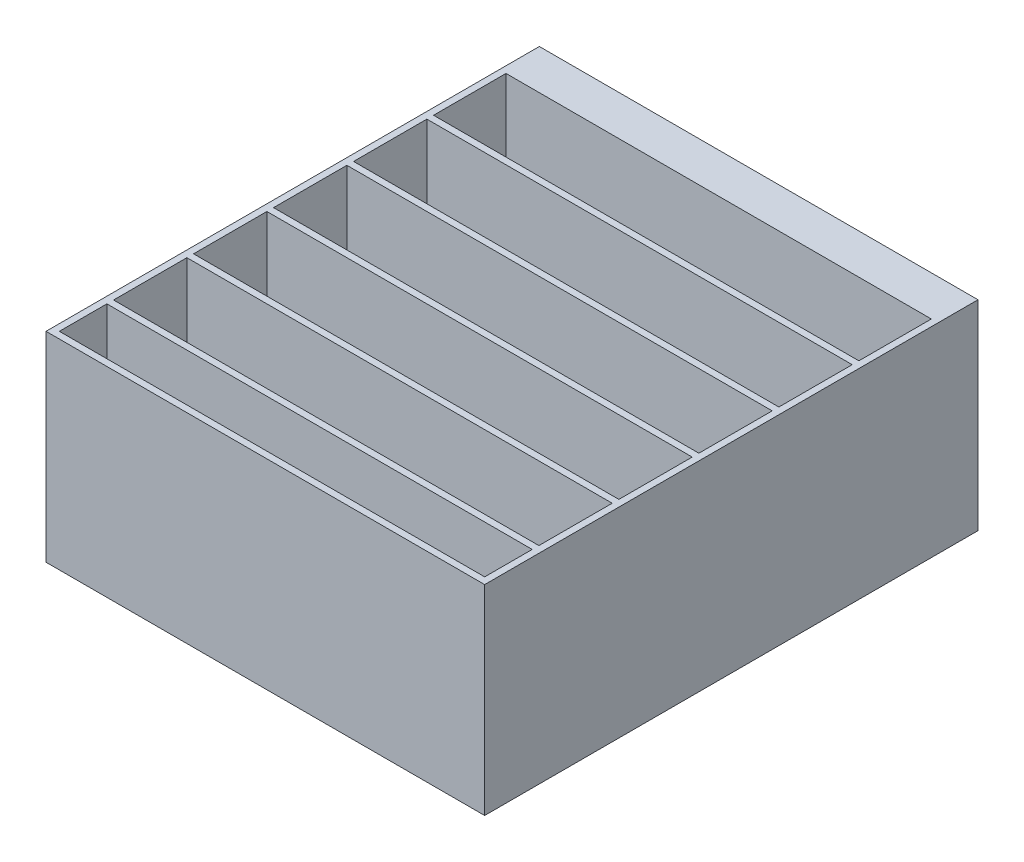
SolidWorks part; units mm, degrees
ref_plane "Plan de face" through (0, 0, 0) normal (0, 0, 1) x (1, 0, 0)
ref_plane "Plan de dessus" through (0, 0, 0) normal (0, 1, 0) x (1, 0, 0)
ref_plane "Plan de droite" through (0, 0, 0) normal (1, 0, 0) x (0, 0, -1)
sketch "Esquisse1" plane through (0, 0, 0) normal (0, 0, 1) x (1, 0, 0)
  line L1 (-108.6783, 23.2404) -> (220.3217, 23.2404)
  line L2 (-108.6783, 23.2404) -> (-108.6783, -126.7596)
  line L3 (-108.6783, -126.7596) -> (220.3217, -126.7596)
  line L4 (220.3217, 23.2404) -> (220.3217, -126.7596)
  dimension "D1" = 329
  dimension "D2" = 150
extrude "Boss.-Extru.1" add sketch "Esquisse1" along normal blind 370
sketch "Esquisse2" plane through (0, 23.2404, 0) normal (0, 1, 0) x (1, 0, 0)
  line L0 (220.3217, 0) -> (-108.6783, 0) construction
  line L1 (-103.6783, -30) -> (215.3217, -30)
  line L2 (-103.6783, -30) -> (-103.6783, -365)
  line L3 (-103.6783, -365) -> (215.3217, -365)
  line L4 (215.3217, -30) -> (215.3217, -365)
  line L5 (-108.6783, -370) -> (-108.6783, 0) construction
  line L6 (220.3217, -370) -> (220.3217, 0) construction
  line L7 (220.3217, -370) -> (-108.6783, -370) construction
  point P10 (220.3217, -185)
  dimension "D1" = 30
  dimension "D2" = 5
  dimension "D3" = 5
  dimension "D4" = 5
extrude "Enlèv. mat.-Extru.1" cut sketch "Esquisse2" against normal blind 90
sketch "Esquisse3" plane through (0, -126.7596, 0) normal (0, -1, 0) x (-1, 0, 0)
  line L0 (108.6783, 0) -> (-220.3217, 0) construction
  line L1 (48.6783, -10.7138) -> (-160.3217, -10.7138)
  line L2 (48.6783, -10.7138) -> (48.6783, 0)
  line L3 (48.6783, 0) -> (-160.3217, 0)
  line L4 (-160.3217, -10.7138) -> (-160.3217, 0)
  line L5 (-220.3217, -370) -> (-220.3217, 0) construction
  line L6 (108.6783, -370) -> (108.6783, 0) construction
  dimension "D1" = 60
  dimension "D2" = 60
extrude "Enlèv. mat.-Extru.2" cut sketch "Esquisse3" against normal blind 30
sketch "Esquisse4" plane through (0, -96.7596, 0) normal (0, -1, 0) x (-1, 0, 0)
  line L0 (-160.3217, 0) -> (-160.3217, -10.7138) construction
  line L1 (-160.2217, -2) -> (48.5783, -2)
  line L2 (-160.2217, -2) -> (-160.2217, -10.7138)
  line L3 (-160.2217, -10.7138) -> (48.5783, -10.7138)
  line L4 (48.5783, -2) -> (48.5783, -10.7138)
  line L5 (48.6783, -10.7138) -> (48.6783, 0) construction
  line L6 (-160.3217, -10.7138) -> (48.6783, -10.7138) construction
  line L7 (48.6783, 0) -> (-160.3217, 0) construction
  point P6 (-160.3217, -5.3569)
  dimension "D1" = 0.1
  dimension "D2" = 0.1
  dimension "D3" = 0
  dimension "D4" = 2
extrude "Enlèv. mat.-Extru.3" cut sketch "Esquisse4" against normal blind 30
sketch "Esquisse6" plane through (0, -66.7596, 0) normal (0, -1, 0) x (-1, 0, 0)
  line L0 (48.6783, -10.7138) -> (48.6783, 0) construction
  line L1 (48.6783, -5.3569) -> (-41.4722, -5.3569)
  line L2 (48.6783, -5.3569) -> (48.6783, -16.759)
  line L3 (48.6783, -16.759) -> (-41.4722, -16.759)
  line L4 (-41.4722, -5.3569) -> (-41.4722, -16.759)
extrude "Boss.-Extru.3" add sketch "Esquisse6" against normal blind 30
sketch "Esquisse7" plane through (-108.6783, 0, 0) normal (-1, 0, 0) x (0, 0, 1)
  line L0 (370, 23.2404) -> (0, 23.2404) construction
  line L1 (84.3399, 23.2404) -> (89.3399, 23.2404)
  line L2 (84.3399, 23.2404) -> (84.3399, -66.7596)
  line L3 (84.3399, -66.7596) -> (89.3399, -66.7596)
  line L4 (89.3399, 23.2404) -> (89.3399, -66.7596)
  line L5 (30, -66.7596) -> (365, -66.7596) construction
  dimension "D1" = 5
extrude "Boss.-Extru.4" add sketch "Esquisse7" against normal blind 329
sketch "Esquisse8" plane through (-108.6783, 0, 0) normal (-1, 0, 0) x (0, 0, 1)
  line L0 (370, 23.2404) -> (0, 23.2404) construction
  line L1 (144.3399, 23.2404) -> (149.3399, 23.2404)
  line L2 (144.3399, 23.2404) -> (144.3399, -69.2576)
  line L3 (144.3399, -69.2576) -> (149.3399, -69.2576)
  line L4 (149.3399, 23.2404) -> (149.3399, -69.2576)
  line L5 (89.3399, -66.7596) -> (89.3399, 23.2404) construction
  dimension "D1" = 5
  dimension "D2" = 55
extrude "Boss.-Extru.5" add sketch "Esquisse8" against normal blind 329
sketch "Esquisse9" plane through (-108.6783, 0, 0) normal (-1, 0, 0) x (0, 0, 1)
  line L0 (370, 23.2404) -> (0, 23.2404) construction
  line L1 (204.3399, 23.2404) -> (209.3399, 23.2404)
  line L2 (204.3399, 23.2404) -> (204.3399, -66.7596)
  line L3 (204.3399, -66.7596) -> (209.3399, -66.7596)
  line L4 (209.3399, 23.2404) -> (209.3399, -66.7596)
  line L5 (149.3399, -66.7596) -> (365, -66.7596) construction
  line L6 (149.3399, -66.7596) -> (149.3399, 23.2404) construction
  dimension "D1" = 5
  dimension "D2" = 55
extrude "Boss.-Extru.6" add sketch "Esquisse9" against normal blind 329
sketch "Esquisse10" plane through (-108.6783, 0, 0) normal (-1, 0, 0) x (0, 0, 1)
  line L0 (370, 23.2404) -> (0, 23.2404) construction
  line L1 (264.3399, 23.2404) -> (269.3399, 23.2404)
  line L2 (264.3399, 23.2404) -> (264.3399, -66.7596)
  line L3 (264.3399, -66.7596) -> (269.3399, -66.7596)
  line L4 (269.3399, 23.2404) -> (269.3399, -66.7596)
  line L5 (209.3399, -66.7596) -> (365, -66.7596) construction
  line L6 (209.3399, -66.7596) -> (209.3399, 23.2404) construction
  dimension "D1" = 5
  dimension "D2" = 55
extrude "Boss.-Extru.7" add sketch "Esquisse10" against normal blind 329
sketch "Esquisse11" plane through (-108.6783, 0, 0) normal (-1, 0, 0) x (0, 0, 1)
  line L0 (370, 23.2404) -> (0, 23.2404) construction
  line L1 (329.3399, -68.6179) -> (324.3399, -68.6179)
  line L2 (329.3399, -68.6179) -> (329.3399, 23.2404)
  line L3 (329.3399, 23.2404) -> (324.3399, 23.2404)
  line L4 (324.3399, -68.6179) -> (324.3399, 23.2404)
  line L5 (269.3399, -66.7596) -> (269.3399, 23.2404) construction
  dimension "D1" = 5
  dimension "D2" = 55
extrude "Boss.-Extru.8" add sketch "Esquisse11" against normal blind 329
